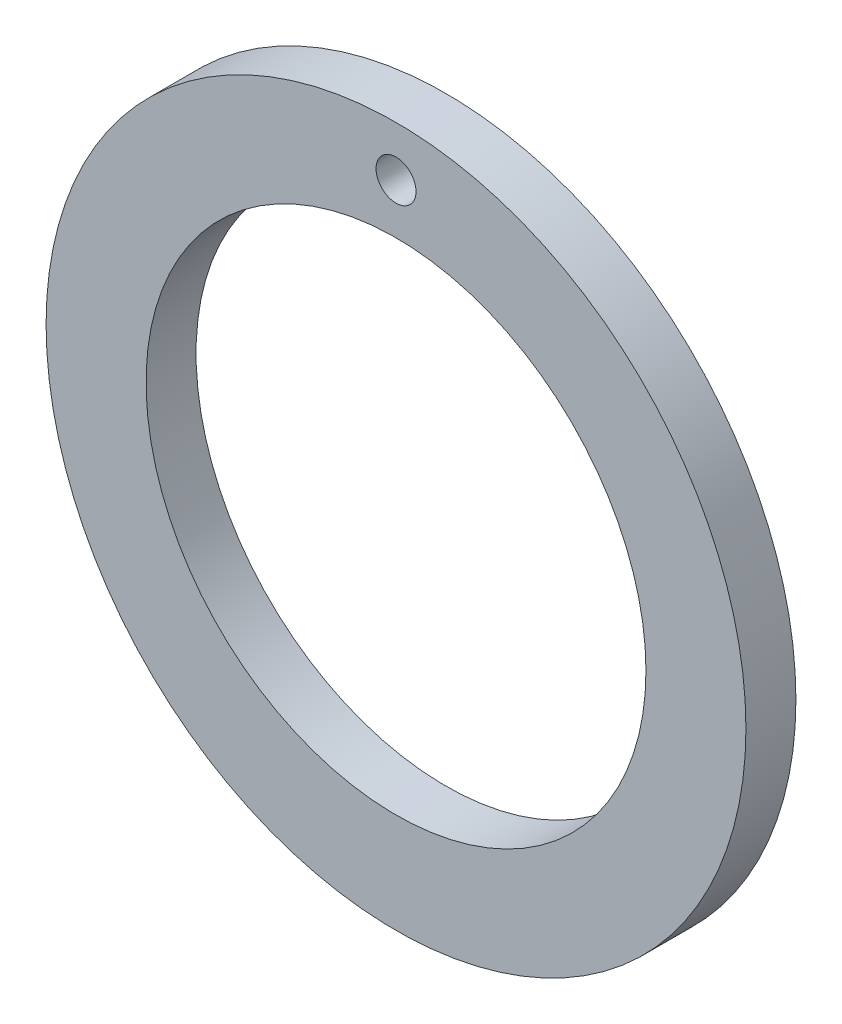
SolidWorks part; units mm, degrees
ref_plane "Front Plane" through (0, 0, 0) normal (0, 0, 1) x (1, 0, 0)
ref_plane "Top Plane" through (0, 0, 0) normal (0, 1, 0) x (1, 0, 0)
ref_plane "Right Plane" through (0, 0, 0) normal (1, 0, 0) x (0, 0, -1)
sketch "Sketch1" plane through (0, 0, 0) normal (0, 0, 1) x (1, 0, 0)
  line L0 (0, 11.1125) -> (0, 7.9375) construction
  circle A0 centre (0, 0) radius 7.9375
  circle A1 centre (0, 0) radius 11.1125
  circle A2 centre (0, 9.525) radius 0.8467
  point P4 (0, -7.9375)
  dimension "ID" = 15.875
  dimension "OD" = 22.225
  dimension "Dowel Hole Diameter" = 1.6933
sketch "Sketch2" plane through (0, 0, 0) normal (1, 0, 0) x (0, 0, -1)
  line L0 (-0.7937, 11.1125) -> (0.7937, 11.1125) construction
  line L1 (0, 11.1125) -> (0, -11.1125) construction
  point P2 (0, 11.1125)
  dimension "Thickness" = 1.5875
sketch "Sketch3" plane through (0, 0, 0) normal (0, 0, 1) x (1, 0, 0)
  line L0 (0, 11.1125) -> (0, 9.525) construction
  line L1 (0, 9.525) -> (0, 7.9375) construction
  circle A0 centre (0, 0) radius 7.9375 construction
  circle A1 centre (0, 0) radius 11.1125 construction
  circle A2 centre (0, 0) radius 7.9375
  circle A3 centre (0, 0) radius 11.1125
  circle A4 centre (0, 9.525) radius 0.635
  dimension "D1" = 1.27
extrude "Boss-Extrude1" add sketch "Sketch3" along normal mid plane 1.5875
equation "\"D1@Sketch3\"=(\"OD@Sketch1\"-\"ID@Sketch1\")*0.2"
equation "\"D1@Boss-Extrude1\"=\"thickness@sketch2\""
